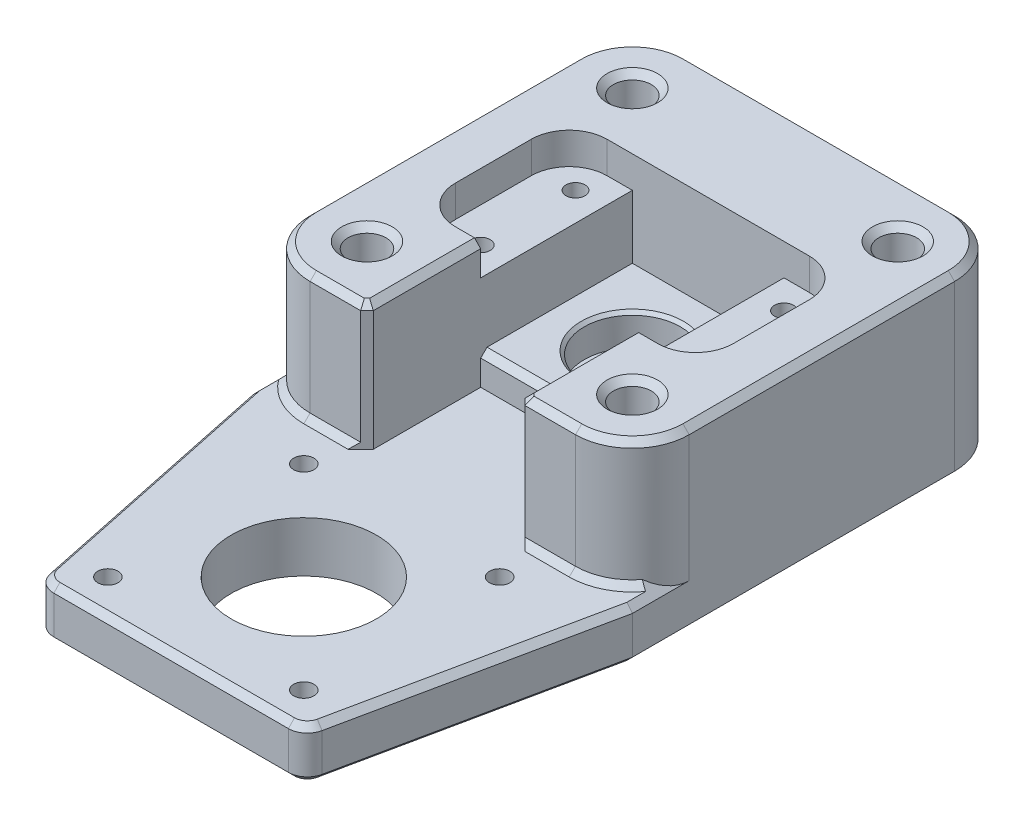
SolidWorks part; units mm, degrees
ref_plane "前视基准面" through (0, 0, 0) normal (0, 0, 1) x (1, 0, 0)
ref_plane "上视基准面" through (0, 0, 0) normal (0, 1, 0) x (1, 0, 0)
ref_plane "右视基准面" through (0, 0, 0) normal (1, 0, 0) x (0, 0, -1)
sketch "草图1" plane through (0, 0, 0) normal (0, 1, 0) x (1, 0, 0)
  line L0 (-30, -7) -> (-21, -50)
  line L1 (-21, -50) -> (21, -50)
  line L2 (-30, -7) -> (-30, 53)
  line L3 (-30, 53) -> (30, 53)
  line L4 (30, -7) -> (30, 53)
  line L9 (-21, -50) -> (21, -50)
  line L13 (30, -7) -> (21, -50)
  point P0 (0, 0)
  point P6 (0, -29)
  dimension "D1" = 60
  dimension "D2" = 43
  dimension "D3" = 60
  dimension "D4" = 0
  dimension "D5" = 43
  dimension "D6" = 9
  dimension "D7" = 42
extrude "凸台-拉伸1" add sketch "草图1" along normal blind 8 contours L13 L4 L3 L2 L0 L1
sketch "草图2" plane through (0, 8, 0) normal (0, 1, 0) x (1, 0, 0)
  line L0 (0, 0) -> (0, 53) construction
  line L2 (-30, 53) -> (-12, 53)
  line L3 (-30, 53) -> (-30, -7)
  line L4 (-30, -7) -> (-12, -7)
  line L5 (-12, 53) -> (-12, -7)
  line L6 (12, 53) -> (12, -7)
  line L7 (30, -7) -> (12, -7)
  line L8 (30, 53) -> (30, -7)
  line L9 (-30, 53) -> (30, 53) construction
  line L10 (30, 53) -> (12, 53)
  circle A0 centre (-21, 44) radius 3
  circle A1 centre (-21, 2) radius 3
  circle A2 centre (21, 2) radius 3
  circle A3 centre (21, 44) radius 3
  dimension "D5" = 9
  dimension "D6" = 0
  dimension "D2" = 6
  dimension "D3" = 6
  dimension "D4" = 9
  dimension "D1" = 18
sketch "草图3" plane through (0, 8, 0) normal (0, 1, 0) x (1, 0, 0)
  line L0 (-21, -50) -> (21, -50) construction
  circle A0 centre (0, -29) radius 11.5
  circle A1 centre (15.5, -13.5) radius 1.6
  circle A2 centre (15.5, -44.5) radius 1.6
  circle A3 centre (-15.5, -44.5) radius 1.6
  circle A4 centre (-15.5, -13.5) radius 1.6
  point P6 (0, -50)
  point P16 (0, -29)
  dimension "D1" = 23
  dimension "D2" = 21
  dimension "D3" = 3.2
  dimension "D4" = 15.5
  dimension "D5" = 15.5
  dimension "D6" = 4
extrude "切除-拉伸1" cut sketch "草图3" against normal blind 20
extrude "凸台-拉伸2" add sketch "草图2" along normal blind 20
sketch "草图4" plane through (0, 8, 0) normal (0, 1, 0) x (1, 0, 0)
  circle A0 centre (0, 23) radius 4.5
  dimension "D1" = 9
extrude "切除-拉伸2" cut sketch "草图4" against normal blind 20
sketch "草图5" plane through (0, 8, 0) normal (0, 1, 0) x (1, 0, 0)
sketch "草图7" plane through (0, 8, 0) normal (0, 1, 0) x (1, 0, 0)
  line L0 (-12, 53) -> (12, 53) construction
  line L4 (-12, -7) -> (-12, 53) construction
  line L5 (12, 35) -> (-12, 35)
  line L6 (12, 35) -> (12, 53)
  line L7 (12, 53) -> (-12, 53)
  line L8 (-12, 35) -> (-12, 53)
  line L9 (12, 35) -> (-12, 53) construction
  line L10 (12, 53) -> (-12, 35) construction
  circle A0 centre (0, 23) radius 4.5 construction
  point P4 (0, 44)
  dimension "D1" = 12
  dimension "D2" = 0
extrude "凸台-拉伸6" add sketch "草图7" along normal up to surface (20 mm away) up to face at (21, 28, -5)
sketch "草图8" plane through (0, 8, 0) normal (0, 1, 0) x (1, 0, 0)
  line L2 (-12, 11) -> (12, 11)
  line L3 (-12, 11) -> (-12, 35)
  line L4 (-12, 35) -> (12, 35)
  line L5 (12, 11) -> (12, 35)
  line L6 (-12, 11) -> (12, 35) construction
  line L7 (-12, 35) -> (12, 11) construction
  circle A0 centre (0, 23) radius 6.5
  point P0 (0, 23)
  dimension "D1" = 13
extrude "凸台-拉伸7" add sketch "草图8" along normal blind 5
sketch "草图9" plane through (0, 0, 0) normal (0, -1, 0) x (1, 0, 0)
  circle A0 centre (0, -23) radius 14.9
  circle A1 centre (0, -23) radius 4.5
  dimension "D1" = 29.8
  dimension "D2" = 9
extrude "凸台-拉伸8" add sketch "草图9" along normal blind 7
sketch "草图12" plane through (0, 0, 0) normal (0, -1, 0) x (1, 0, 0)
  circle A0 centre (0, -23) radius 17.5
  circle A1 centre (0, -23) radius 15
  dimension "D1" = 35
extrude "凸台-拉伸10" add sketch "草图12" along normal blind 0.4
sketch "草图13" plane through (0, -7, 0) normal (0, -1, 0) x (1, 0, 0)
  circle A0 centre (0, -23) radius 7.6
  dimension "D1" = 15.2
extrude "切除-拉伸4" cut sketch "草图13" against normal blind 5
fillet "圆角2" radius 9 2 edges at (-30, 14, -53) (30, 14, -53)
sketch "草图14" plane through (0, 28, 0) normal (0, 1, 0) x (1, 0, 0)
  line L0 (-30, 2) -> (-30, -7)
  line L1 (-30, -7) -> (-21, -7)
  line L2 (21, -7) -> (30, -7)
  line L3 (30, -7) -> (30, 2)
  arc A0 (-30, 2) -> (-21, -7) centre (-21, 2) ccw
  arc A1 (21, -7) -> (30, 2) centre (21, 2) ccw
extrude "切除-拉伸5" cut sketch "草图14" against normal up to surface (20 mm away) up to face at (15.5, 8, 15.1)
sketch "草图17" plane through (0, 0, 0) normal (0, -1, 0) x (1, 0, 0)
  circle A0 centre (-15.5, 13.5) radius 3
  circle A1 centre (-15.5, 44.5) radius 3
  circle A2 centre (15.5, 44.5) radius 3
  circle A3 centre (15.5, 13.5) radius 3
  point P12 (0, 29)
  dimension "D1" = 6
  dimension "D2" = 4
extrude "切除-拉伸8" cut sketch "草图17" against normal blind 3
fillet "圆角3" radius 3 2 edges at (21, 4, 50) (-21, 4, 50)
chamfer "倒角3" distance 1 angle 45 10 edges at (-20.4545, 0, 49.3285) (-25.7496, 0, 27.3073) (0, 0, 50) (20.4545, 0, 49.3285) (25.7496, 0, 27.3073) (30, 0, -18.5) (27.364, 0, -50.364) (0, 0, -53) (-27.364, 0, -50.364) (-30, 0, -18.5)
chamfer "倒角4" distance 1 angle 45 2 edges at (12, 18, 7) (-12, 18, 7)
chamfer "倒角8" distance 1 angle 45 1 edges at (0, 13, -11)
chamfer "倒角11" distance 1 angle 44 7 edges at (30, 8, 2.5) (25.7496, 8, 27.3073) (20.4545, 8, 49.3285) (0, 8, 50) (-20.4545, 8, 49.3285) (-30, 8, 2.5) (-25.7496, 8, 27.3073)
chamfer "倒角12" distance 1 angle 44 4 edges at (25.7169, 8, 5.6649) (17, 8, 7) (-17, 8, 7) (-25.7169, 8, 5.6649)
sketch "草图18" plane through (0, 28, 0) normal (0, 1, 0) x (1, 0, 0)
  line L1 (-16, 35) -> (16, 35)
  line L2 (-22, 29) -> (-22, 17)
  line L3 (-16, 11) -> (16, 11)
  line L4 (22, 29) -> (22, 17)
  line L5 (-22, 35) -> (22, 11) construction
  line L6 (-22, 11) -> (22, 35) construction
  arc A0 (16, 11) -> (22, 17) centre (16, 17) ccw
  arc A1 (16, 35) -> (22, 29) centre (16, 29) cw
  arc A2 (-22, 17) -> (-16, 11) centre (-16, 17) ccw
  arc A3 (-16, 35) -> (-22, 29) centre (-16, 29) ccw
  point P0 (0, 23)
  dimension "D3" = 6
  dimension "D1" = 24
  dimension "D2" = 44
extrude "切除-拉伸9" cut sketch "草图18" against normal blind 5
sketch "草图19" plane through (0, 23, 0) normal (0, 1, 0) x (1, 0, 0)
  line L0 (-12, 35) -> (-12, 12) construction
  line L1 (-12, 35) -> (-16, 35) construction
  line L2 (-16, 11) -> (-12, 11) construction
  line L3 (12, 35) -> (12, 11) construction
  line L4 (12, 11) -> (16, 11) construction
  line L5 (-16, 35) -> (16, 35) construction
  line L6 (12, 12) -> (12, 35) construction
  circle A0 centre (16.5, 30.5) radius 1.5
  circle A1 centre (16.5, 15.5) radius 1.5
  circle A2 centre (-16.5, 30.5) radius 1.5
  circle A3 centre (-16.5, 15.5) radius 1.5
  dimension "D1" = 3
  dimension "D2" = 3
  dimension "D3" = 4.5
  dimension "D4" = 4.5
  dimension "D5" = 4.5
  dimension "D6" = 4.5
  dimension "D7" = 3
  dimension "D8" = 3
  dimension "D9" = 4.5
  dimension "D10" = 4.5
  dimension "D11" = 4.5
  dimension "D12" = 4.5
extrude "切除-拉伸10" cut sketch "草图19" against normal blind 10
chamfer "倒角14" distance 0.5 angle 45 1 edges at (0, -7, -37.9)
chamfer "倒角15" distance 1 angle 45 17 edges at (-21, 28, 1) (-21, 28, -41) (21, 28, -47) (21, 28, -5) (-12, 28, -2.5) (-12.5, 28, 6.5) (-17, 28, 7) (-27.364, 28, 4.364) (-30, 28, -23) (-27.364, 28, -50.364) (0, 28, -53) (12, 28, -2.5) (12.5, 28, 6.5) (17, 28, 7) (27.364, 28, 4.364) (27.364, 28, -50.364) (30, 28, -23)
chamfer "倒角16" distance 0.5 angle 45 1 edges at (0, -7, -30.6)
sketch "草图20" plane through (0, 13, 0) normal (0, 1, 0) x (1, 0, 0)
  circle A0 centre (0, 23) radius 7.6
extrude "切除-拉伸11" cut sketch "草图20" against normal blind 5
chamfer "倒角17" distance 0.5 angle 45 1 edges at (0, 13, -15.4)
